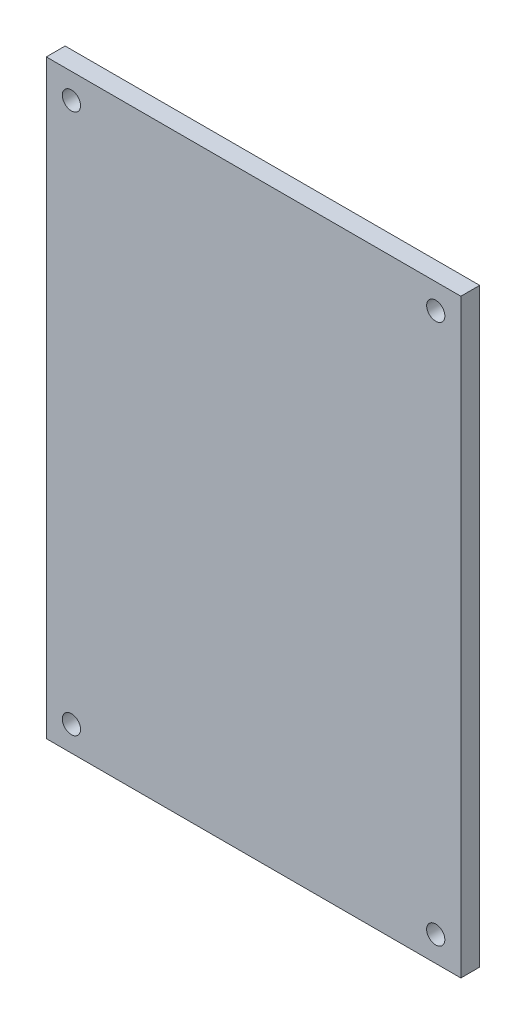
SolidWorks part; units mm, degrees
ref_plane "Front Plane" through (0, 0, 0) normal (0, 0, 1) x (1, 0, 0)
ref_plane "Top Plane" through (0, 0, 0) normal (0, 1, 0) x (1, 0, 0)
ref_plane "Right Plane" through (0, 0, 0) normal (1, 0, 0) x (0, 0, -1)
sketch "Sketch1" plane through (0, 0, 0) normal (0, 0, 1) x (1, 0, 0)
  line L4 (0, -45.7348) -> (0, 48.2652) construction
  line L32 (-33, 48.2652) -> (33, 48.2652)
  line L33 (-33, 48.2652) -> (-33, -45.7348)
  line L34 (-33, -45.7348) -> (33, -45.7348)
  line L35 (33, 48.2652) -> (33, -45.7348)
  circle A0 centre (29, -41.7348) radius 1.45
  circle A1 centre (29, 44.2652) radius 1.45
  circle A2 centre (-29, -41.7348) radius 1.45
  circle A3 centre (-29, 44.2652) radius 1.45
  point P0 (0, 0)
  point P1 (-29, 44.2652)
  point P12 (-7.0796, -16.4523)
  point P15 (-7.0796, -16.4523)
  point P32 (0, 39.5291)
  dimension "D3" = 4
  dimension "D10" = 2.9
  dimension "D11" = 2.9
  dimension "D13" = 2.9
  dimension "D2" = 86
  dimension "D4" = 4
  dimension "D5" = 4
  dimension "D6" = 4
  dimension "D12" = 58
  dimension "D15" = 58
extrude "Boss-Extrude1" add sketch "Sketch1" along normal blind 3
